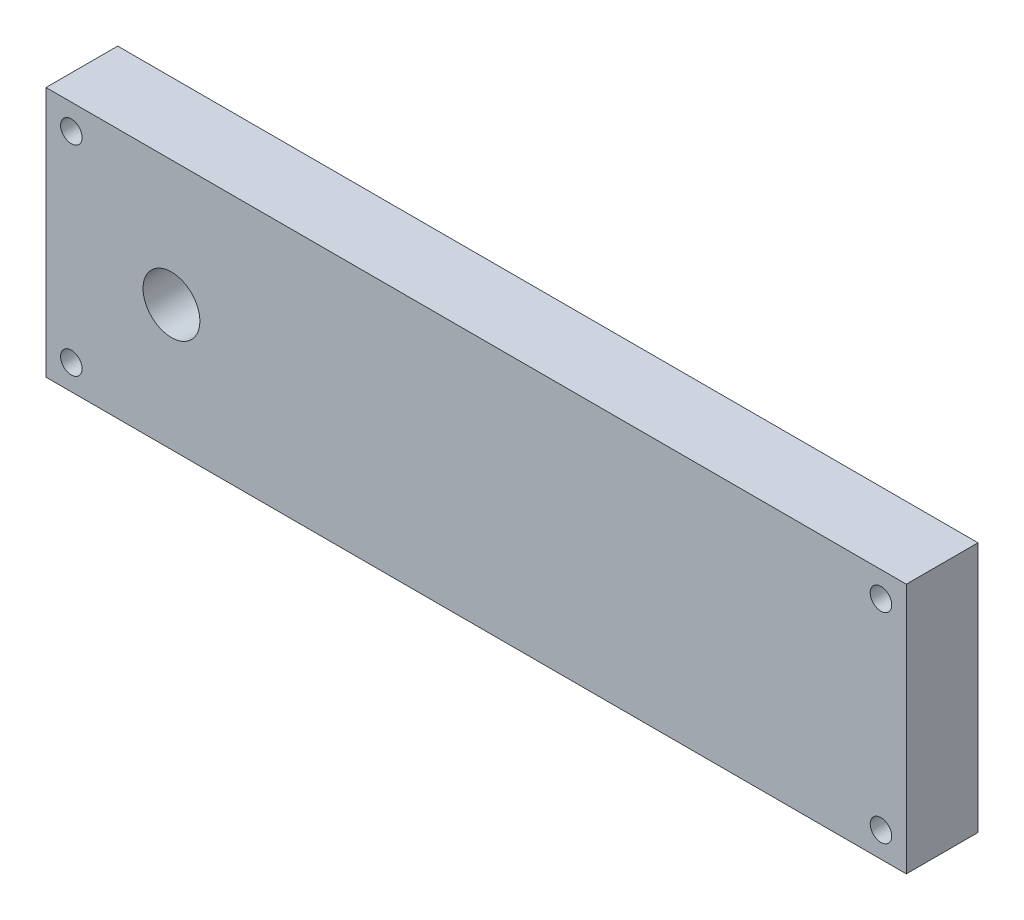
SolidWorks part; units mm, degrees
ref_plane "Front Plane" through (0, 0, 0) normal (0, 0, 1) x (1, 0, 0)
ref_plane "Top Plane" through (0, 0, 0) normal (0, 1, 0) x (1, 0, 0)
ref_plane "Right Plane" through (0, 0, 0) normal (1, 0, 0) x (0, 0, -1)
sketch "Sketch2" plane through (0, 0, 0) normal (0, 0, 1) x (1, 0, 0)
  line L1 (-33.4091, 14.8295) -> (86.5909, 14.8295)
  line L2 (-33.4091, 14.8295) -> (-33.4091, -20.1705)
  line L3 (-33.4091, -20.1705) -> (86.5909, -20.1705)
  line L4 (86.5909, 14.8295) -> (86.5909, -20.1705)
  line L5 (-33.4091, -2.6705) -> (1.5909, -2.6705) construction
  line L6 (-15.9091, 14.8295) -> (-15.9091, -20.1705) construction
  line L7 (-33.4091, 14.8295) -> (1.5909, -20.1705) construction
  line L8 (1.5909, 14.8295) -> (-33.4091, -20.1705) construction
  line L9 (26.5909, 14.8295) -> (26.5909, -20.1705) construction
  circle A0 centre (-29.8736, -16.6349) radius 1.5
  circle A1 centre (-15.9091, -2.6705) radius 3.965
  circle A2 centre (83.0554, 11.294) radius 1.5
  circle A3 centre (-29.8736, 11.294) radius 1.5
  circle A4 centre (83.0554, -16.6349) radius 1.5
  point P4 (26.5909, -2.6705)
  dimension "D4" = 5
  dimension "D5" = 3
  dimension "D6" = 7.93
  dimension "D1" = 120
  dimension "D2" = 35
  dimension "D3" = 35
extrude "Boss-Extrude1" add sketch "Sketch2" along normal blind 10
